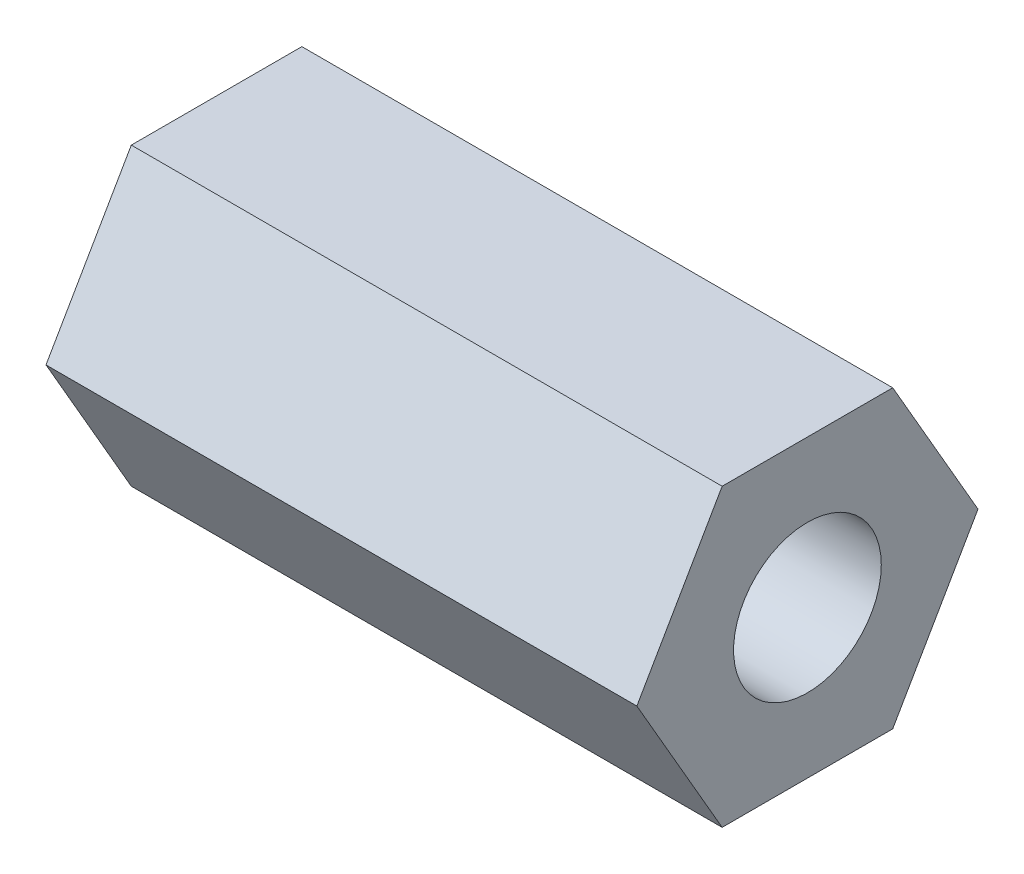
SolidWorks part; units mm, degrees
ref_plane "Front Plane" through (0, 0, 0) normal (0, 0, 1) x (1, 0, 0)
ref_plane "Top Plane" through (0, 0, 0) normal (0, 1, 0) x (1, 0, 0)
ref_plane "Right Plane" through (0, 0, 0) normal (1, 0, 0) x (0, 0, -1)
sketch "Sketch1" plane through (0, 0, 0) normal (1, 0, 0) x (0, 0, -1)
  line L1 (2.8868, 0) -> (1.4434, 2.5)
  line L2 (1.4434, 2.5) -> (-1.4434, 2.5)
  line L3 (-1.4434, 2.5) -> (-2.8868, 0)
  line L4 (-2.8868, 0) -> (-1.4434, -2.5)
  line L5 (-1.4434, -2.5) -> (1.4434, -2.5)
  line L6 (1.4434, -2.5) -> (2.8868, 0)
  circle A0 centre (0, 0) radius 2.5 construction
  circle A1 centre (0, 0) radius 1.25
  dimension "D1" = 5
  dimension "D2" = 2.5
extrude "Boss-Extrude2" add sketch "Sketch1" along normal blind 10
